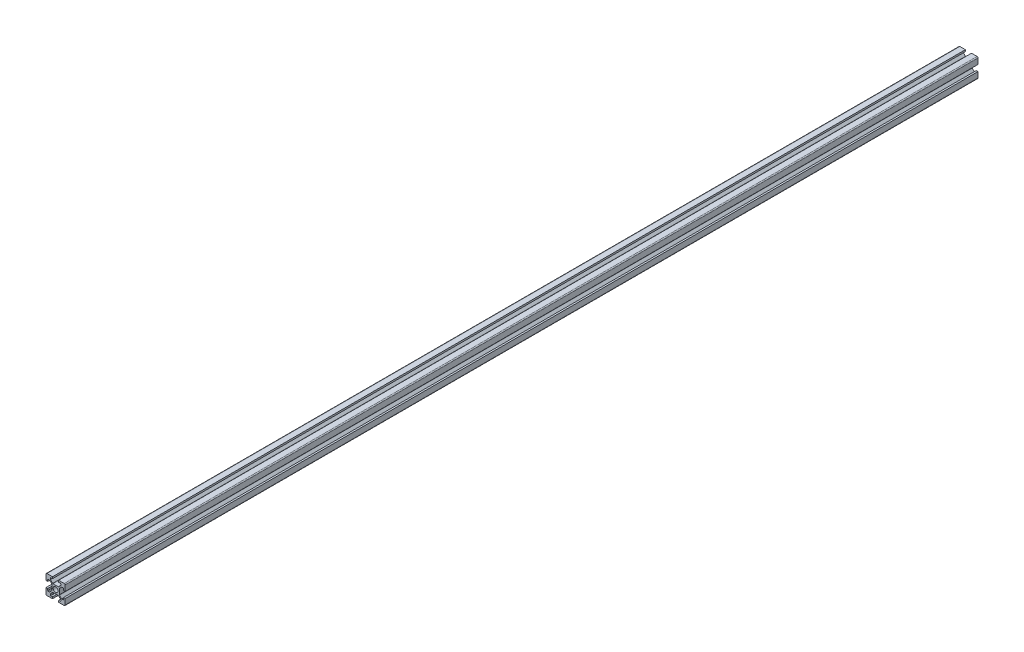
SolidWorks part; units mm, degrees
material "1060 Alloy"
ref_plane "Front Plane" through (0, 0, 0) normal (0, 0, 1) x (1, 0, 0)
ref_plane "Top Plane" through (0, 0, 0) normal (0, 1, 0) x (1, 0, 0)
ref_plane "Right Plane" through (0, 0, 0) normal (1, 0, 0) x (0, 0, -1)
sketch "Sketch1" plane through (0, 0, 0) normal (0, 0, 1) x (1, 0, 0)
  line L0 (20, 0) -> (-8.059, 28.059) construction
  line L1 (0, 0) -> (6.8, 0)
  line L2 (0, 0) -> (0, 6.8)
  line L3 (0, 20) -> (6.8, 20)
  line L4 (20, 0) -> (20, 6.8)
  line L5 (6.8, 20) -> (6.8, 18.2)
  line L6 (20, 20) -> (8.2322, 8.2322) construction
  line L7 (12.95, 6.1) -> (7.05, 6.1)
  line L8 (13.9, 7.05) -> (13.9, 12.95)
  line L9 (12.95, 13.9) -> (7.05, 13.9)
  line L10 (6.1, 7.05) -> (6.1, 12.95)
  line L11 (13.9, 6.1) -> (6.1, 13.9) construction
  line L12 (13.9, 13.9) -> (6.1, 6.1) construction
  line L13 (4.55, 16.4) -> (7.05, 13.9)
  line L14 (13.2, 18.2) -> (13.2, 20)
  line L15 (1.8, 6.8) -> (0, 6.8)
  line L16 (0, 13.2) -> (0, 20)
  line L17 (0, 13.2) -> (1.8, 13.2)
  line L18 (10, 10) -> (10, 13.9) construction
  line L19 (16.4, 4.55) -> (13.9, 7.05)
  line L20 (4.55, 16.4) -> (4.55, 18.2)
  line L21 (4.55, 18.2) -> (6.8, 18.2)
  line L22 (13.2, 18.2) -> (15.45, 18.2)
  line L23 (15.45, 18.2) -> (15.45, 16.4)
  line L24 (15.45, 16.4) -> (12.95, 13.9)
  line L25 (16.4, 4.55) -> (18.2, 4.55)
  line L26 (18.2, 4.55) -> (18.2, 6.8)
  line L27 (20, 6.8) -> (18.2, 6.8)
  line L28 (18.2, 13.2) -> (20, 13.2)
  line L29 (18.2, 13.2) -> (18.2, 15.45)
  line L30 (18.2, 15.45) -> (16.4, 15.45)
  line L31 (16.4, 15.45) -> (13.9, 12.95)
  line L32 (1.8, 4.55) -> (3.6, 4.55)
  line L33 (3.6, 15.45) -> (6.1, 12.95)
  line L34 (3.6, 15.45) -> (1.8, 15.45)
  line L35 (1.8, 15.45) -> (1.8, 13.2)
  line L36 (0, 13.2) -> (1.8, 13.2)
  line L37 (1.8, 6.8) -> (0, 6.8)
  line L38 (3.6, 4.55) -> (6.1, 7.05)
  line L39 (1.8, 6.8) -> (1.8, 4.55)
  line L40 (15.45, 3.6) -> (12.95, 6.1)
  line L41 (4.55, 3.6) -> (7.05, 6.1)
  line L42 (4.55, 1.8) -> (4.55, 3.6)
  line L43 (6.8, 1.8) -> (4.55, 1.8)
  line L44 (6.8, 1.8) -> (6.8, 0)
  line L45 (15.45, 3.6) -> (15.45, 1.8)
  line L46 (15.45, 1.8) -> (13.2, 1.8)
  line L47 (13.2, 0) -> (13.2, 1.8)
  line L48 (13.2, 20) -> (20, 20)
  line L49 (20, 13.2) -> (20, 20)
  line L50 (13.2, 0) -> (20, 0)
  line L51 (6.1, 6.1) -> (-5.5045, -5.5045) construction
  circle A0 centre (10, 10) radius 2.5
  point P25 (10, 16.4)
  point P39 (13.2, 19.1)
  point P46 (0.9, 6.8)
  dimension "D3" = 5
  dimension "D2" = 20
  dimension "D4" = 7.8
  dimension "D5" = 7.8
  dimension "D6" = 6.8
  dimension "D7" = 6.8
  dimension "D8" = 1.8
  dimension "D9" = 10.9
  dimension "D10" = 1.8
  dimension "D11" = 10.9
  dimension "D12" = 20
extrude "Boss-Extrude1" add sketch "Sketch1" along normal blind 955 contours L47 L50 L4 L27 L26 L25 L19 L8 L31 L30 L29 L28 L49 L48 L14 L22 L23 L24 L9 L13 L20 L21 L5 L3 L16 L17 L35 L34 L33 L10 L38 L32 L39 L15 L2 L1 L44 L43 L42 L41 L7 L40 L45 L46 A0
fillet "Fillet1" radius 1 4 edges at (20, 20, 477.5) (20, 0, 477.5) (0, 0, 477.5) (0, 20, 477.5)
fillet "Fillet2" radius 0.5 6 edges at (4.55, 18.2, 477.5) (4.55, 16.4, 477.5) (7.05, 13.9, 477.5) (15.45, 18.2, 477.5) (15.45, 16.4, 477.5) (12.95, 13.9, 477.5)
fillet "Fillet3" radius 0.5 6 edges at (18.2, 15.45, 477.5) (16.4, 15.45, 477.5) (13.9, 12.95, 477.5) (18.2, 4.55, 477.5) (13.9, 7.05, 477.5) (16.4, 4.55, 477.5)
fillet "Fillet4" radius 0.5 6 edges at (1.8, 15.45, 477.5) (3.6, 15.45, 477.5) (6.1, 12.95, 477.5) (3.6, 4.55, 477.5) (1.8, 4.55, 477.5) (6.1, 7.05, 477.5)
fillet "Fillet5" radius 0.5 6 edges at (7.05, 6.1, 477.5) (4.55, 3.6, 477.5) (4.55, 1.8, 477.5) (15.45, 1.8, 477.5) (15.45, 3.6, 477.5) (12.95, 6.1, 477.5)
